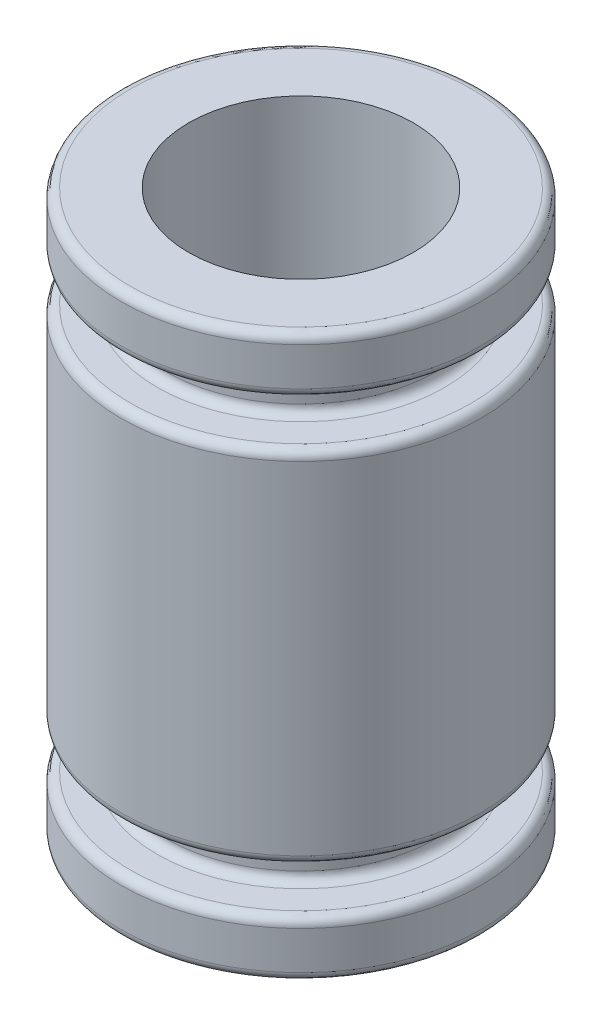
SolidWorks part; units mm, degrees
ref_plane "Front Plane" through (0, 0, 0) normal (0, 0, 1) x (1, 0, 0)
ref_plane "Top Plane" through (0, 0, 0) normal (0, 1, 0) x (1, 0, 0)
ref_plane "Right Plane" through (0, 0, 0) normal (1, 0, 0) x (0, 0, -1)
sketch "Sketch1" plane through (0, 0, 0) normal (0, 0, 1) x (1, 0, 0)
  line L0 (0, 0) -> (0, -7310.5131) construction
  line L1 (0, 6.25) -> (-4, 6.25)
  line L2 (-4, 6.25) -> (-4, 5)
  line L3 (-4, 5) -> (-3, 5)
  line L4 (-3, 5) -> (-3, 4)
  line L5 (-0.1858, 0) -> (-50000.1858, 0) construction
  line L6 (0, -6.25) -> (0, 6.25)
  line L7 (-3, 4) -> (-4, 4)
  line L8 (-4, 4) -> (-4, -4)
  line L9 (-3, -4) -> (-4, -4)
  line L10 (-3, -5) -> (-3, -4)
  line L11 (-4, -5) -> (-3, -5)
  line L12 (-4, -6.25) -> (-4, -5)
  line L13 (0, -6.25) -> (-4, -6.25)
  point P14 (-4, 0)
  point P16 (0, 0)
  dimension "D1" = 4
  dimension "D2" = 1
  dimension "D3" = 6.25
  dimension "D4" = 4
  dimension "D5" = 1
revolve "Revolve1" add sketch "Sketch1" angle 360 about L6
fillet "Fillet1" radius 0.2 10 edges at (3, -4, 0) (3, -5, 0) (4, -6.25, 0) (4, -5, 0) (4, -4, 0) (3, 5, 0) (3, 4, 0) (4, 4, 0) (4, 5, 0) (4, 6.25, 0)
sketch "Sketch2" plane through (0, 6.25, 0) normal (0, 1, 0) x (1, 0, 0)
  circle A0 centre (0, 0) radius 2.5
  dimension "D1" = 5
extrude "Cut-Extrude1" cut sketch "Sketch2" against normal through all
